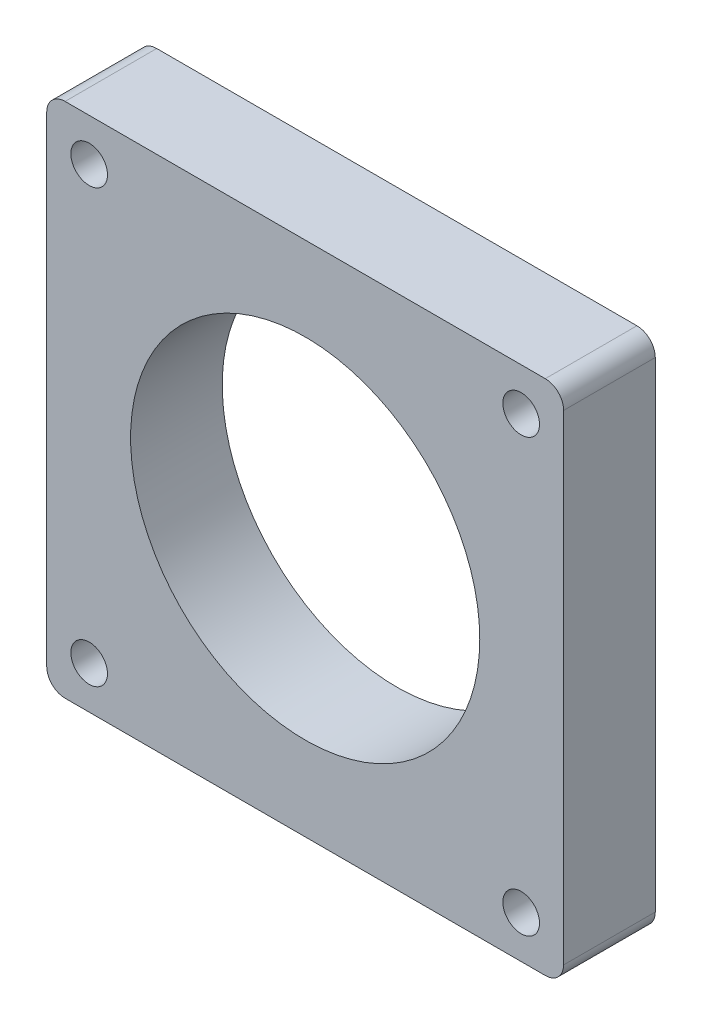
SolidWorks part; units mm, degrees
ref_plane "Plan de face" through (0, 0, 0) normal (0, 0, 1) x (1, 0, 0)
ref_plane "Plan de dessus" through (0, 0, 0) normal (0, 1, 0) x (1, 0, 0)
ref_plane "Plan de droite" through (0, 0, 0) normal (1, 0, 0) x (0, 0, -1)
sketch "Esquisse1" plane through (0, 0, 0) normal (0, 0, 1) x (1, 0, 0)
  line L0 (0, 0) -> (0, 40.0403) construction
  line L1 (-28.2, -28.2) -> (28.2, -28.2)
  line L2 (-28.2, -28.2) -> (-28.2, 28.2)
  line L3 (-28.2, 28.2) -> (28.2, 28.2)
  line L4 (28.2, -28.2) -> (28.2, 28.2)
  line L5 (-28.2, -28.2) -> (28.2, 28.2) construction
  line L6 (-28.2, 28.2) -> (28.2, -28.2) construction
  line L7 (0, 0) -> (80.9815, 0) construction
  circle A0 centre (23.57, 23.57) radius 2
  circle A1 centre (-23.57, 23.57) radius 2
  circle A2 centre (23.57, -23.57) radius 2
  circle A3 centre (-23.57, -23.57) radius 2
  point P0 (0, 0)
  dimension "D3" = 23.57
  dimension "D4" = 23.57
  dimension "D5" = 4
  dimension "D1" = 56.4
  dimension "D2" = 56.4
extrude "Boss.-Extru.1" add sketch "Esquisse1" along normal blind 10
sketch "Esquisse2" plane through (0, 0, 10) normal (0, 0, 1) x (1, 0, 0)
  circle A0 centre (0, 0) radius 19.05
  dimension "D1" = 38.1
extrude "Enlèv. mat.-Extru.1" cut sketch "Esquisse2" against normal blind 10
fillet "Congé1" radius 2 4 edges at (-28.2, -28.2, 5) (28.2, -28.2, 5) (-28.2, 28.2, 5) (28.2, 28.2, 5)
